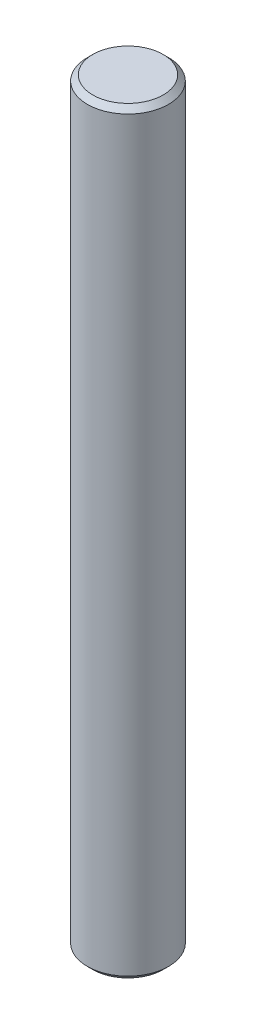
SolidWorks part; units mm, degrees
ref_plane "Front Plane" through (0, 0, 0) normal (0, 0, 1) x (1, 0, 0)
ref_plane "Top Plane" through (0, 0, 0) normal (0, 1, 0) x (1, 0, 0)
ref_plane "Right Plane" through (0, 0, 0) normal (1, 0, 0) x (0, 0, -1)
sketch "Sketch1" plane through (0, 0, 0) normal (0, 1, 0) x (1, 0, 0)
  circle A0 centre (0, 0) radius 1.5
  dimension "D1" = 3
extrude "Boss-Extrude1" add sketch "Sketch1" along normal mid plane 28
chamfer "Chamfer1" distance 0.2 angle 45 2 edges at (0, -14, 1.5) (0, 14, 1.5)
